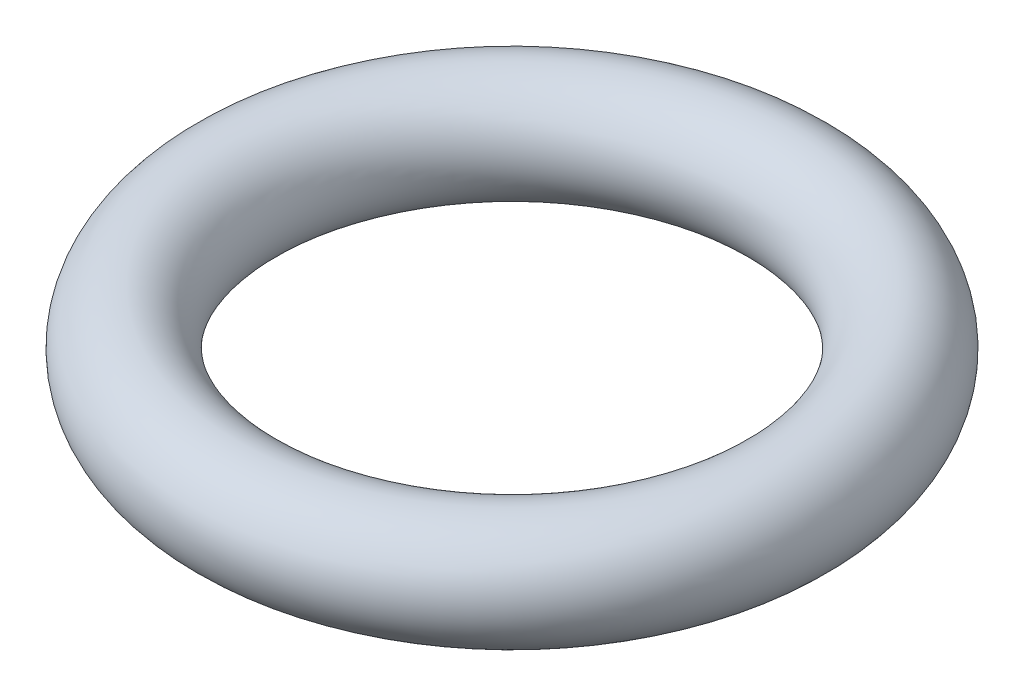
SolidWorks part; units mm, degrees
ref_plane "Alzado" through (0, 0, 0) normal (0, 0, 1) x (1, 0, 0)
ref_plane "Planta" through (0, 0, 0) normal (0, 1, 0) x (1, 0, 0)
ref_plane "Vista lateral" through (0, 0, 0) normal (1, 0, 0) x (0, 0, -1)
sketch "Croquis1" plane through (0, 0, 0) normal (0, 0, 1) x (1, 0, 0)
  line L0 (0, 0) -> (0, -4.5021) construction
  circle A0 centre (5, 0) radius 1
  dimension "D1" = 2
  dimension "D2" = 5
revolve "Revolución1" add sketch "Croquis1" angle 360 about L0
